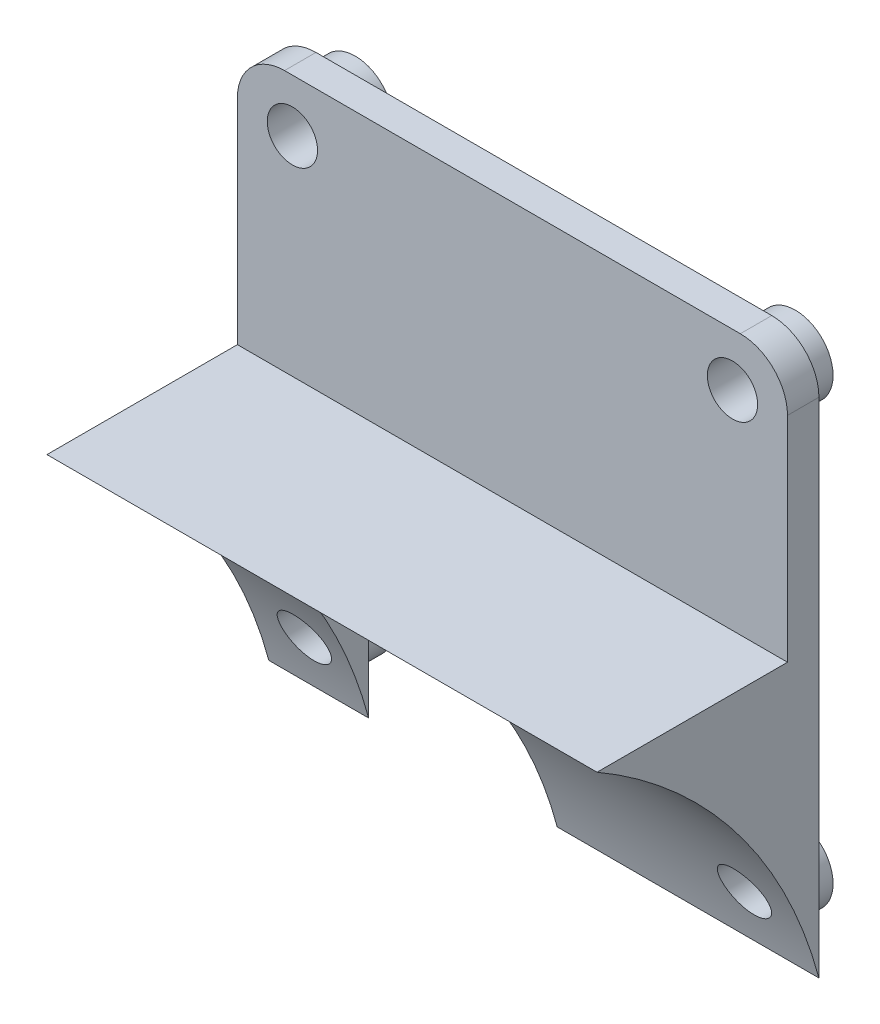
SolidWorks part; units mm, degrees
ref_plane "Alzado" through (0, 0, 0) normal (0, 0, 1) x (1, 0, 0)
ref_plane "Planta" through (0, 0, 0) normal (0, 1, 0) x (1, 0, 0)
ref_plane "Vista lateral" through (0, 0, 0) normal (1, 0, 0) x (0, 0, -1)
sketch "Croquis3" plane through (0, 0, 0) normal (1, 0, 0) x (0, 0, -1)
  line L0 (0, 0) -> (15.15, 26.2406) construction
  line L2 (0, 0) -> (29.2676, 7.8422) construction
  line L4 (0, 0) -> (39.9929, 0) construction
  line L5 (15.15, 26.2406) -> (27.2676, 26.2406)
  line L7 (29.2676, 7.8422) -> (29.2676, 42.8422)
  line L8 (29.2676, 42.8422) -> (27.2676, 42.8422)
  line L9 (27.2676, 26.2406) -> (27.2676, 42.8422)
  arc A0 (29.2676, 7.8422) -> (15.15, 26.2406) centre (0, 0) ccw
  dimension "D1" = 45
  dimension "D2" = 15
  dimension "D3" = 35
  dimension "D4" = 2
extrude "Saliente-Extruir1" add sketch "Croquis3" along normal blind 35
sketch "Croquis4" plane through (0, 0, -29.2676) normal (0, 0, -1) x (-1, 0, 0)
  line L0 (-35, 7.8422) -> (0, 7.8422) construction
  line L1 (-25, 19.8422) -> (-10, 19.8422) construction
  line L3 (-17.5, 7.8422) -> (-17.5, 19.8422) construction
  circle A0 centre (-25, 19.8422) radius 2
  circle A1 centre (-10, 19.8422) radius 2
  dimension "D3" = 4
  dimension "D1" = 15
  dimension "D2" = 12
extrude "Cortar-Extruir1" cut sketch "Croquis4" against normal blind 2
sketch "Croquis5" plane through (0, 0, -27.2676) normal (0, 0, -1) x (-1, 0, 0)
  circle A0 centre (-10, 19.8422) radius 2 construction
  circle A1 centre (-25, 19.8422) radius 2 construction
  circle A2 centre (-10, 19.8422) radius 2 construction
  circle A3 centre (-25, 19.8422) radius 2 construction
  circle A4 centre (-25, 19.8422) radius 1.25
  circle A5 centre (-10, 19.8422) radius 1.25
  dimension "D1" = 0.75
extrude "Cortar-Extruir2" cut sketch "Croquis5" against normal through all
sketch "Croquis6" plane through (0, 0, -29.2676) normal (0, 0, -1) x (-1, 0, 0)
  line L0 (-35, 7.8422) -> (0, 7.8422) construction
  line L1 (-6.35, 7.8422) -> (-18.35, 7.8422)
  line L2 (-6.35, 7.8422) -> (-6.35, 15.8422)
  line L3 (-6.35, 15.8422) -> (-18.35, 15.8422)
  line L4 (-18.35, 7.8422) -> (-18.35, 15.8422)
  line L5 (0, 7.8422) -> (0, 42.8422) construction
  dimension "D1" = 6.35
  dimension "D2" = 12
  dimension "D3" = 8
extrude "Cortar-Extruir3" cut sketch "Croquis6" against normal through all
sketch "Croquis7" plane through (0, 0, -29.2676) normal (0, 0, -1) x (-1, 0, 0)
  line L4 (-17.5, 42.8422) -> (-17.5, 39.4922) construction
  line L5 (-35, 42.8422) -> (0, 42.8422) construction
  line L6 (-31.5, 39.4922) -> (-3.5, 39.4922) construction
  circle A0 centre (-31.5, 39.4922) radius 1.6
  circle A1 centre (-31.5, 11.4922) radius 1.6
  circle A2 centre (-3.5, 11.4922) radius 1.6
  circle A3 centre (-3.5, 39.4922) radius 1.6
  circle A4 centre (-31.5, 39.4922) radius 2.4
  circle A5 centre (-3.5, 39.4922) radius 2.4
  circle A6 centre (-3.5, 11.4922) radius 2.4
  circle A7 centre (-31.5, 11.4922) radius 2.4
  dimension "D1" = 3.2
  dimension "D4" = 3.35
  dimension "D2" = 28
  dimension "D3" = 28
  dimension "D6" = 0.8
extrude "Saliente-Extruir3" add sketch "Croquis7" along normal blind 2
sketch "Croquis10" plane through (0, 0, -29.2676) normal (0, 0, -1) x (-1, 0, 0)
  circle A0 centre (-31.5, 11.4922) radius 1.6 construction
  circle A1 centre (-3.5, 11.4922) radius 1.6 construction
  circle A2 centre (-3.5, 39.4922) radius 1.6 construction
  circle A3 centre (-31.5, 39.4922) radius 1.6 construction
  circle A4 centre (-31.5, 11.4922) radius 1.6
  circle A5 centre (-3.5, 11.4922) radius 1.6
  circle A6 centre (-3.5, 39.4922) radius 1.6
  circle A7 centre (-31.5, 39.4922) radius 1.6
extrude "Cortar-Extruir6" cut sketch "Croquis10" against normal through all
fillet "Redondeo1" radius 3 2 edges at (35, 42.8422, -28.2676) (0, 42.8422, -28.2676)
